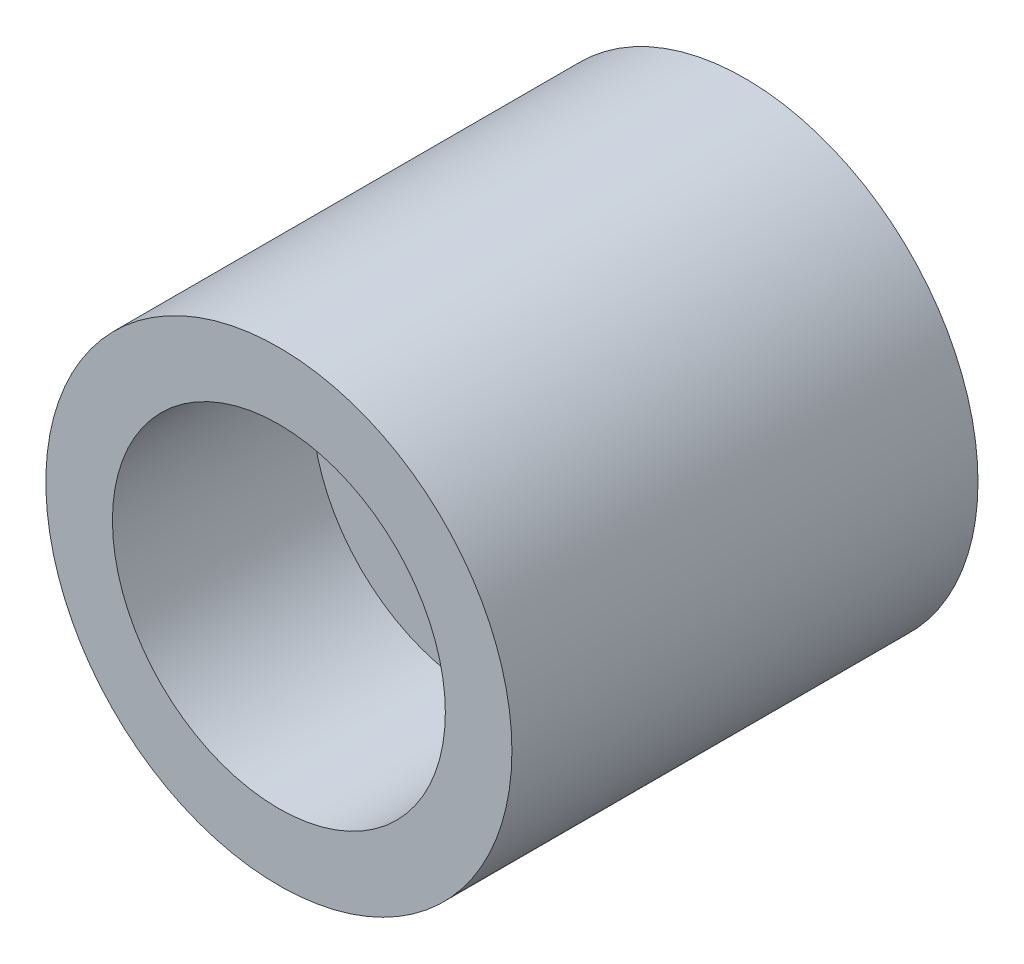
SolidWorks part; units mm, degrees
material "Cast Carbon Steel"
ref_plane "Front Plane" through (0, 0, 0) normal (0, 0, 1) x (1, 0, 0)
ref_plane "Top Plane" through (0, 0, 0) normal (0, 1, 0) x (1, 0, 0)
ref_plane "Right Plane" through (0, 0, 0) normal (1, 0, 0) x (0, 0, -1)
sketch "Sketch1" plane through (0, 0, 0) normal (0, 0, 1) x (1, 0, 0)
  circle A0 centre (0, 0) radius 88.9
  dimension "D1" = 177.8
extrude "Boss-Extrude1" add sketch "Sketch1" along normal blind 177.8
sketch "Sketch2" plane through (0, 0, 177.8) normal (0, 0, 1) x (1, 0, 0)
  circle A0 centre (0, 0) radius 63.5
  dimension "D1" = 127
extrude "Cut-Extrude1" cut sketch "Sketch2" against normal blind 76.2
sketch "Sketch3" plane through (0, 0, 0) normal (0, 0, -1) x (-1, 0, 0)
  circle A0 centre (0, 0) radius 63.5
  dimension "D1" = 127
extrude "Cut-Extrude2" cut sketch "Sketch3" against normal blind 76.2
